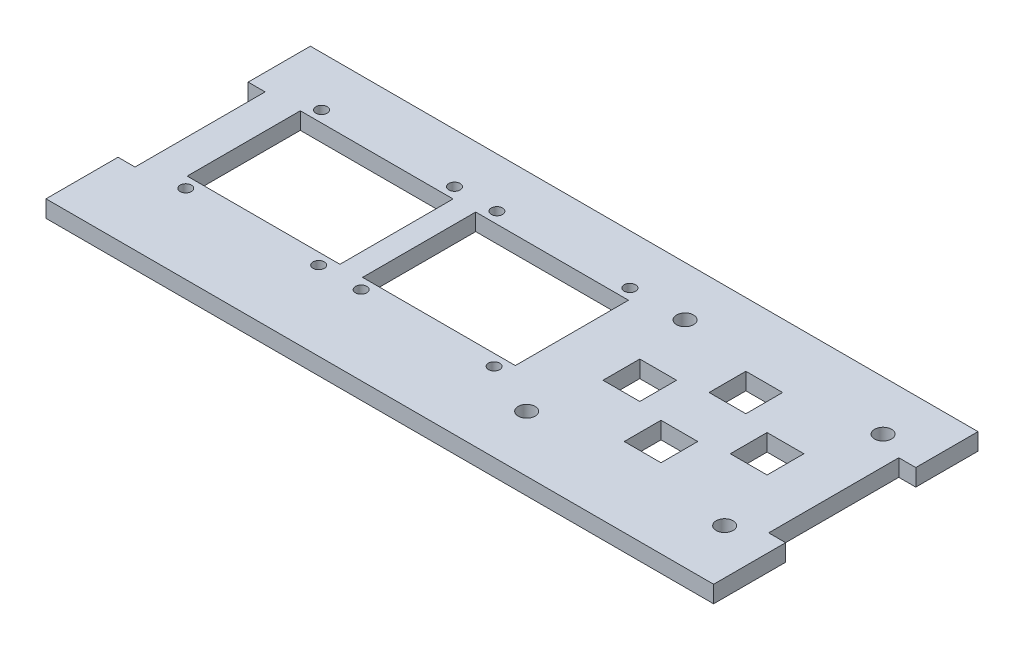
SolidWorks part; units mm, degrees
material "Acrylic (Medium-high impact)"
ref_plane "Front Plane" through (0, 0, 0) normal (0, 0, 1) x (1, 0, 0)
ref_plane "Top Plane" through (0, 0, 0) normal (0, 1, 0) x (1, 0, 0)
ref_plane "Right Plane" through (0, 0, 0) normal (1, 0, 0) x (0, 0, -1)
sketch "Sketch1" plane through (0, 0, 0) normal (0, 1, 0) x (1, 0, 0)
  line L0 (-55.5482, -6.1514) -> (-52.5482, -6.1514)
  line L1 (-55.5482, 27.8486) -> (62.4518, 27.8486)
  line L2 (-55.5482, 27.8486) -> (-55.5482, 16.8486)
  line L3 (-55.5482, -18.8814) -> (62.4518, -18.8814)
  line L4 (62.4518, 27.8486) -> (62.4518, 16.8486)
  line L5 (-15.5482, -2.9307) -> (11.4518, -2.9307)
  line L6 (-46.5482, 17.0693) -> (-19.5482, 17.0693)
  line L7 (-46.5482, 17.0693) -> (-46.5482, -2.9307)
  line L8 (-46.5482, -2.9307) -> (-19.5482, -2.9307)
  line L9 (-55.5482, 16.8486) -> (-52.5482, 16.8486)
  line L10 (-52.5482, 16.8486) -> (-52.5482, -6.1514)
  line L11 (62.4518, 16.8486) -> (59.4518, 16.8486)
  line L12 (59.4518, 16.8486) -> (59.4518, -6.1514)
  line L13 (59.4518, -6.1514) -> (62.4518, -6.1514)
  line L14 (62.4518, -6.1514) -> (62.4518, -18.8814)
  line L15 (-55.5482, -6.1514) -> (-55.5482, -18.8814)
  line L16 (-19.5482, 17.0693) -> (-19.5482, -2.9307)
  line L20 (32.7018, 16.5693) -> (39.2018, 16.5693)
  line L21 (32.7018, 16.5693) -> (32.7018, 10.0693)
  line L26 (32.7018, 10.0693) -> (39.2018, 10.0693)
  line L27 (39.2018, 16.5693) -> (39.2018, 10.0693)
  line L28 (43.9518, 9.0693) -> (50.4518, 9.0693)
  line L29 (43.9518, 9.0693) -> (43.9518, 2.5693)
  line L34 (43.9518, 2.5693) -> (50.4518, 2.5693)
  line L35 (50.4518, 9.0693) -> (50.4518, 2.5693)
  line L36 (32.7018, 1.5693) -> (39.2018, 1.5693)
  line L37 (32.7018, 1.5693) -> (32.7018, -4.9307)
  line L41 (32.7018, -4.9307) -> (39.2018, -4.9307)
  line L42 (39.2018, 1.5693) -> (39.2018, -4.9307)
  line L43 (21.4518, 9.0693) -> (27.9518, 9.0693)
  line L45 (21.4518, 9.0693) -> (21.4518, 2.5693)
  line L47 (21.4518, 2.5693) -> (27.9518, 2.5693)
  line L49 (11.4518, 17.0693) -> (11.4518, -2.9307)
  line L50 (-15.5482, 17.0693) -> (11.4518, 17.0693)
  line L51 (-15.5482, 17.0693) -> (-15.5482, -2.9307)
  line L52 (27.9518, 9.0693) -> (27.9518, 2.5693)
  circle A0 centre (19.4518, 19.0693) radius 1.5
  circle A1 centre (54.4518, 19.0693) radius 1.5
  circle A2 centre (54.4518, -8.9307) radius 1.5
  circle A3 centre (19.4518, -8.9307) radius 1.5
  circle A4 centre (9.7018, 19.0693) radius 1
  circle A5 centre (9.7018, -4.9307) radius 1
  circle A6 centre (-13.7982, -4.9307) radius 1
  circle A7 centre (-13.7982, 19.0693) radius 1
  circle A8 centre (-44.7982, 19.0693) radius 1
  circle A9 centre (-21.2982, 19.0693) radius 1
  circle A10 centre (-44.7982, -4.9307) radius 1
  circle A11 centre (-21.2982, -4.9307) radius 1
  dimension "D7" = 20
  dimension "D9" = 1
  dimension "D24" = 28
  dimension "D27" = 3
  dimension "D29" = 6
  dimension "D36" = 2
  dimension "D3" = 46.73
  dimension "D5" = 27
  dimension "D6" = 118
  dimension "D8" = 24
  dimension "D12" = 3
  dimension "D13" = 3
  dimension "D15" = 16
  dimension "D17" = 35
  dimension "D18" = 8.5
  dimension "D19" = 6.5
  dimension "D10" = 31.5
  dimension "D11" = 4.75
  dimension "D23" = 2
  dimension "D25" = 11.5
  dimension "D26" = 8
  dimension "D30" = 4
  dimension "D33" = 2
  dimension "D37" = 23.5
  dimension "D40" = 1.75
  dimension "D41" = 23
extrude "Boss-Extrude1" add sketch "Sketch1" along normal blind 3
